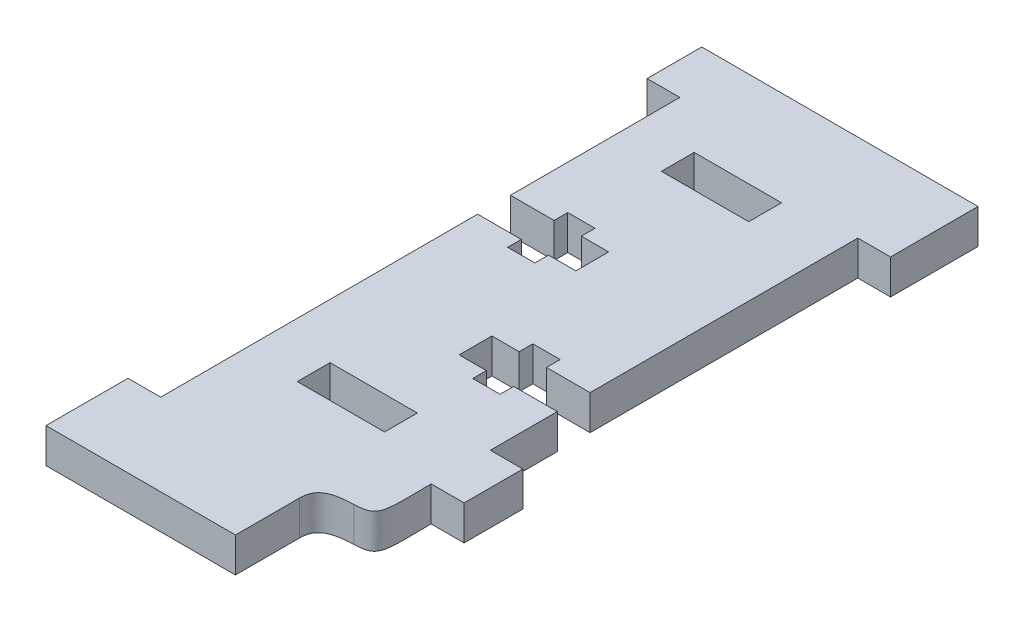
SolidWorks part; units mm, degrees
ref_plane "Front Plane" through (0, 0, 0) normal (0, 0, 1) x (1, 0, 0)
ref_plane "Top Plane" through (0, 0, 0) normal (0, 1, 0) x (1, 0, 0)
ref_plane "Right Plane" through (0, 0, 0) normal (1, 0, 0) x (0, 0, -1)
sketch "Sketch1" plane through (0, 0, 0) normal (0, 1, 0) x (1, 0, 0)
  line L2 (8.4508, -13.3816) -> (8.4069, -13.382)
  line L3 (8.4069, -13.382) -> (5.4327, -13.382)
  line L4 (5.4327, -13.382) -> (5.4765, -13.3816)
  line L5 (5.4765, -13.3816) -> (5.4765, -7.2515)
  line L6 (5.4765, -7.2515) -> (1.4836, -7.2515)
  line L7 (1.4836, -7.2515) -> (1.4836, -8.5015)
  line L8 (1.4836, -8.5015) -> (-1.012, -8.5015)
  line L9 (-1.012, -8.5015) -> (-1.012, -7.2515)
  line L10 (-1.012, -7.2515) -> (-3.5076, -7.2515)
  line L11 (-3.5076, -7.2515) -> (-3.5076, -4.2514)
  line L12 (-3.5076, -4.2514) -> (-1.012, -4.2514)
  line L13 (-1.012, -4.2514) -> (-1.012, -3.0013)
  line L14 (-1.012, -3.0013) -> (1.4836, -3.0013)
  line L15 (1.4836, -3.0013) -> (1.4836, -4.2514)
  line L16 (1.4836, -4.2514) -> (5.4765, -4.2514)
  line L17 (5.4765, -4.2514) -> (5.4765, 20.2464)
  line L18 (5.4765, 20.2464) -> (8.4712, 20.2464)
  line L19 (8.4712, 20.2464) -> (8.4712, 28.2467)
  line L20 (8.4712, 28.2467) -> (-16.8046, 28.2467)
  line L21 (-16.8046, 28.2467) -> (-16.8046, 23.2465)
  line L22 (-16.8046, 23.2465) -> (-13.8099, 23.2465)
  line L23 (-13.8099, 23.2465) -> (-13.8099, 7.746)
  line L24 (-13.8099, 7.746) -> (-9.817, 7.746)
  line L25 (-9.817, 7.746) -> (-9.817, 8.9961)
  line L26 (-9.817, 8.9961) -> (-7.3214, 8.9961)
  line L27 (-7.3214, 8.9961) -> (-7.3214, 7.746)
  line L28 (-7.3214, 7.746) -> (-4.8258, 7.746)
  line L29 (-4.8258, 7.746) -> (-4.8258, 4.7459)
  line L30 (-4.8258, 4.7459) -> (-7.3214, 4.7459)
  line L31 (-7.3214, 4.7459) -> (-7.3214, 3.4958)
  line L32 (-7.3214, 3.4958) -> (-9.817, 3.4958)
  line L33 (-9.817, 3.4958) -> (-9.817, 4.7459)
  line L34 (-9.817, 4.7459) -> (-13.8099, 4.7459)
  line L35 (-13.8099, 4.7459) -> (-13.8099, -24.2553)
  line L36 (-13.8099, -24.2553) -> (-16.8046, -24.2553)
  line L37 (-16.8046, -24.2553) -> (-16.8046, -31.7556)
  line L38 (-16.8046, -31.7556) -> (0.5295, -31.7556)
  line L39 (0.5295, -31.7556) -> (0.5295, -25.876)
  line L40 (8.4508, -18.7551) -> (8.4508, -13.3816)
  line L41 (-0.8123, 19.5486) -> (-0.8123, 16.5484)
  line L42 (-0.8123, 16.5484) -> (-8.7981, 16.5484)
  line L43 (-8.7981, 16.5484) -> (-8.7981, 19.5486)
  line L44 (-8.7981, 19.5486) -> (-0.8123, 19.5486)
  line L45 (-0.8123, -13.7721) -> (-0.8123, -16.7722)
  line L46 (-0.8123, -16.7722) -> (-8.7981, -16.7722)
  line L47 (-8.7981, -16.7722) -> (-8.7981, -13.7721)
  line L48 (-8.7981, -13.7721) -> (-0.8123, -13.7721)
  spline S2 degree 3 poles (0.5295, -25.876) (0.5295, -24.2161) (1.8842, -23.9808) (3.5436, -23.9159) knots 38 38 38 38 39 39 39 39
  spline S3 degree 3 poles (3.5436, -23.9159) (5.6513, -23.8333) (5.4823, -23.2775) (5.4327, -18.7551) knots 39 39 39 39 40 40 40 40
  spline S4 degree 3 poles (5.4327, -18.7551) (6.3246, -18.7551) (7.369, -18.7551) (8.4508, -18.7551) knots 40 40 40 40 41 41 41 41
  point P0 (0, 0)
extrude "Boss-Extrude1" add sketch "Sketch1" along normal blind 3.175
